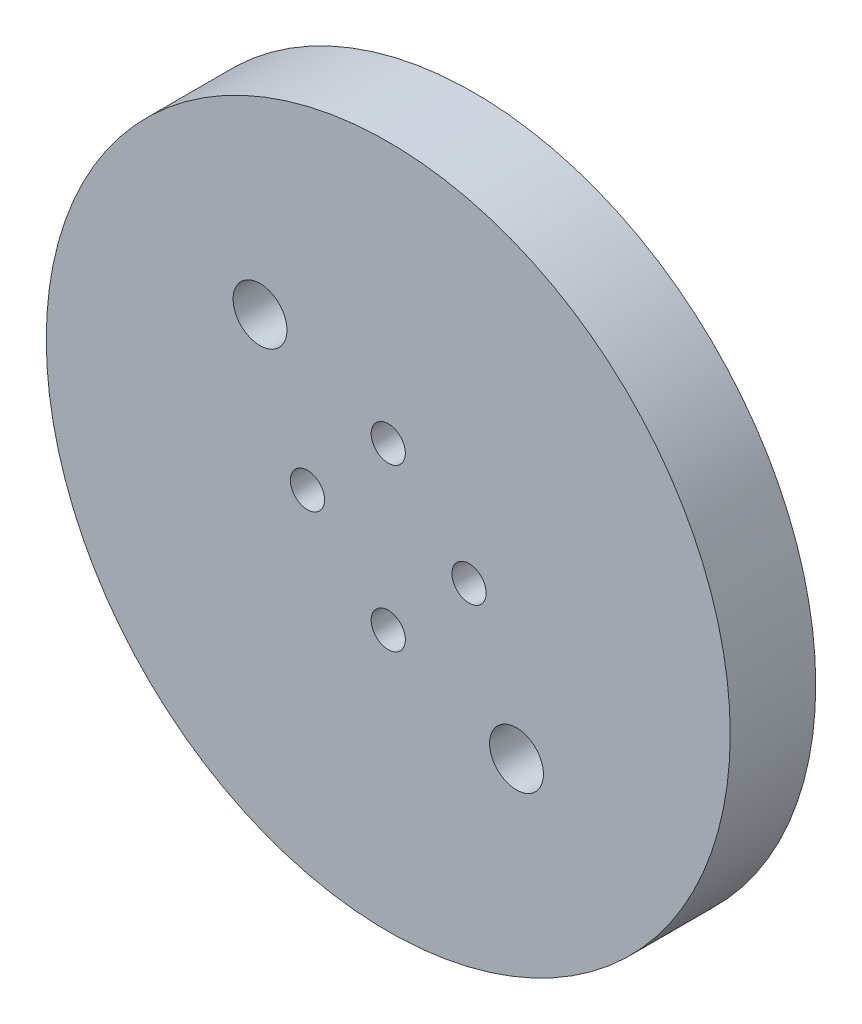
SolidWorks part; units mm, degrees
ref_plane "Front Plane" through (0, 0, 0) normal (0, 0, 1) x (1, 0, 0)
ref_plane "Top Plane" through (0, 0, 0) normal (0, 1, 0) x (1, 0, 0)
ref_plane "Right Plane" through (0, 0, 0) normal (1, 0, 0) x (0, 0, -1)
sketch "Sketch1" plane through (0, 0, 0) normal (0, 0, 1) x (1, 0, 0)
  line L0 (-169.7289, -50.8) -> (169.7289, -50.8) construction
  line L1 (-110.0162, 50.8) -> (110.0162, 50.8) construction
  circle A0 centre (0, 0) radius 50.8
  circle A2 centre (12, 0) radius 2.54
  circle A6 centre (0, -12) radius 2.54
  circle A7 centre (-12, 0) radius 2.54
  circle A8 centre (0, 12) radius 2.54
  point P7 (0, -50.8)
  point P14 (0, 50.8)
  point P22 (0, 0)
  dimension "D1" = 101.6
  dimension "D2" = 5.08
  dimension "D5" = 12
  dimension "D6" = 4
extrude "Boss-Extrude1" add sketch "Sketch1" along normal blind 12.7
sketch "Sketch2" plane through (0, 0, 0) normal (0, 0, 1) x (1, 0, 0)
  circle A3 centre (19.05, -19.05) radius 4
  dimension "D1" = 8
  dimension "D2" = 19.05
  dimension "D3" = 19.05
extrude "Cut-Extrude1" cut sketch "Sketch2" along normal through all
sketch "Sketch3" plane through (0, 0, 0) normal (0, 0, 1) x (1, 0, 0)
  circle A0 centre (19.05, -19.05) radius 12.7
  dimension "D1" = 25.4
extrude "Cut-Extrude2" cut sketch "Sketch3" along normal blind 6.35
sketch "Sketch4" plane through (0, 0, 0) normal (0, 0, 1) x (1, 0, 0)
  circle A0 centre (-19.05, 19.05) radius 4
  dimension "D3" = 8
  dimension "D1" = 19.05
  dimension "D2" = 19.05
extrude "Cut-Extrude3" cut sketch "Sketch4" along normal through all
sketch "Sketch5" plane through (0, 0, 0) normal (0, 0, 1) x (1, 0, 0)
  circle A0 centre (-19.05, 19.05) radius 12.7
  dimension "D1" = 25.4
extrude "Cut-Extrude5" cut sketch "Sketch5" along normal blind 6.35
